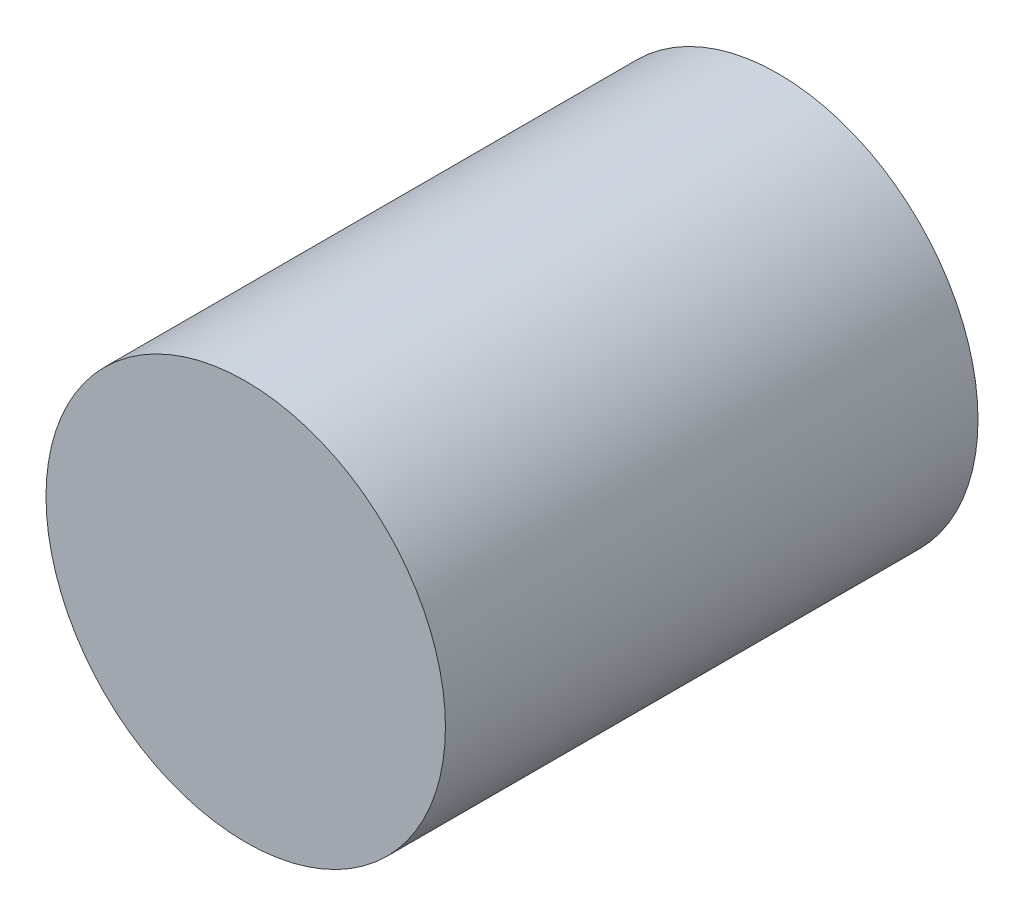
SolidWorks part; units mm, degrees
ref_plane "Front Plane" through (0, 0, 0) normal (0, 0, 1) x (1, 0, 0)
ref_plane "Top Plane" through (0, 0, 0) normal (0, 1, 0) x (1, 0, 0)
ref_plane "Right Plane" through (0, 0, 0) normal (1, 0, 0) x (0, 0, -1)
sketch "Sketch1" plane through (0, 0, 0) normal (0, 0, 1) x (1, 0, 0)
  circle A0 centre (0, 0) radius 7.5
  dimension "D1" = 15
extrude "Boss-Extrude1" add sketch "Sketch1" along normal blind 20
